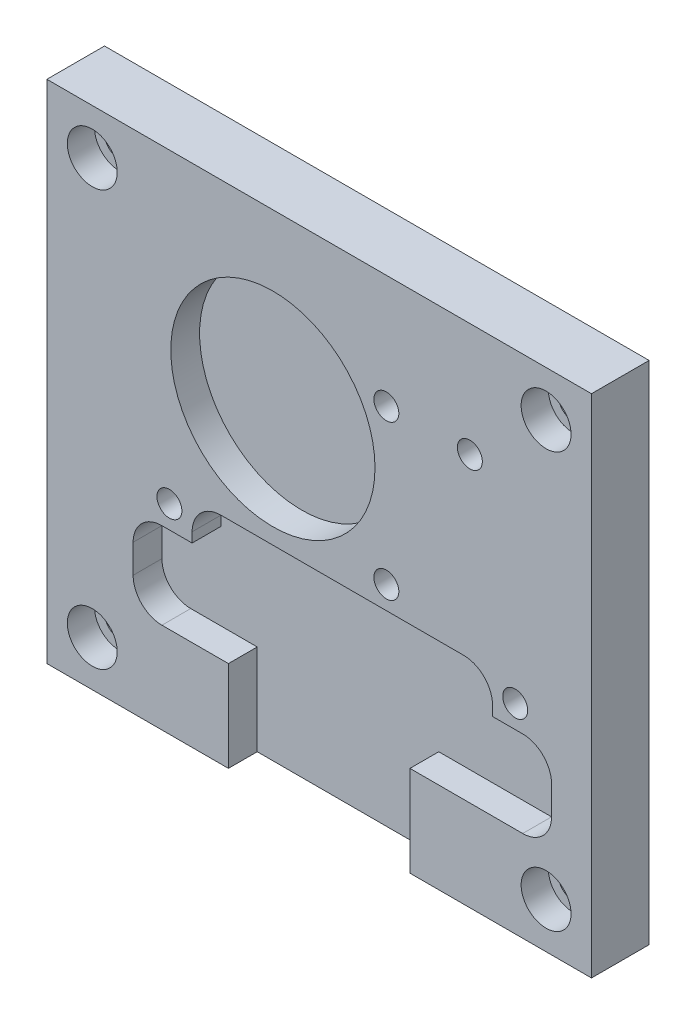
SolidWorks part; units mm, degrees
ref_plane "Front Plane" through (0, 0, 0) normal (0, 0, 1) x (1, 0, 0)
ref_plane "Top Plane" through (0, 0, 0) normal (0, 1, 0) x (1, 0, 0)
ref_plane "Right Plane" through (0, 0, 0) normal (1, 0, 0) x (0, 0, -1)
sketch "Sketch1" plane through (0, 0, 0) normal (0, 0, 1) x (1, 0, 0)
  line L0 (-28, -8.25) -> (-28, -35.75) construction
  line L1 (-60, -55.75) -> (60, -55.75)
  line L2 (-60, -55.75) -> (-60, 55.75)
  line L3 (-60, 55.75) -> (60, 55.75)
  line L4 (60, -55.75) -> (60, 55.75)
  line L5 (-60, -55.75) -> (60, 55.75) construction
  line L6 (-60, 55.75) -> (60, -55.75) construction
  line L7 (-28, -8.25) -> (38.2, -8.25) construction
  line L8 (38.2, -8.25) -> (38.2, -35.75) construction
  line L9 (-38, 55.75) -> (-38, -55.75) construction
  line L10 (48.2, 55.75) -> (48.2, -55.75) construction
  line L11 (-38, 35.75) -> (48.2, 35.75) construction
  line L12 (-28, -35.75) -> (-20, -35.75) construction
  line L13 (-20, -35.75) -> (-20, -55.75) construction
  line L14 (20, -35.75) -> (20, -55.75) construction
  line L15 (20, -35.75) -> (38.2, -35.75) construction
  line L16 (-20, -35.75) -> (20, -35.75) construction
  circle A0 centre (-50, 45.75) radius 10 construction
  circle A1 centre (-50, -45.75) radius 10 construction
  circle A2 centre (50, -45.75) radius 10 construction
  circle A3 centre (50, 45.75) radius 10 construction
  circle A4 centre (43.2, -11.75) radius 2.5 construction
  circle A5 centre (33.2, 30.75) radius 2.5 construction
  circle A6 centre (14.8, 30.75) radius 2.5 construction
  circle A7 centre (14.8, -3.25) radius 2.5 construction
  circle A8 centre (-33, -11.75) radius 2.5 construction
  circle A9 centre (-10.2, 17.75) radius 22.5 construction
  point P0 (0, 0)
  point P40 (0, -35.75)
  point P41 (0, 0)
  dimension "D2" = 20
  dimension "D3" = 5
  dimension "D4" = 45
  dimension "D1" = 100
  dimension "D5" = 10
  dimension "D6" = 18.4
  dimension "D7" = 25
  dimension "D8" = 34
  dimension "D9" = 47.8
  dimension "D10" = 8.5
  dimension "D11" = 13
  dimension "D12" = 14.8
  dimension "D13" = 5
  dimension "D14" = 5
  dimension "D15" = 5
  dimension "D16" = 5
  dimension "D17" = 5
  dimension "D18" = 18
  dimension "D19" = 27.5
  dimension "D20" = 40
extrude "Boss-Extrude1" add sketch "Sketch1" along normal blind 12.7
sketch "Sketch2" plane through (0, 0, 12.7) normal (0, 0, 1) x (1, 0, 0)
  line L0 (38.2, -8.25) -> (38.2, -35.75) construction
  line L1 (20, -35.75) -> (38.2, -35.75) construction
  line L2 (20, -35.75) -> (20, -55.75) construction
  line L3 (-28, -35.75) -> (-20, -35.75) construction
  line L4 (-20, -35.75) -> (-20, -55.75) construction
  line L5 (-28, -8.25) -> (38.2, -8.25) construction
  line L6 (-28, -8.25) -> (-28, -35.75) construction
  line L7 (38.2, -8.25) -> (38.2, -16.75)
  line L8 (20, -35.75) -> (38.2, -35.75)
  line L9 (20, -35.75) -> (20, -55.75)
  line L10 (-28, -35.75) -> (-20, -35.75)
  line L11 (-20, -35.75) -> (-20, -55.75)
  line L12 (-28, -8.25) -> (38.2, -8.25)
  line L13 (-28, -8.25) -> (-28, -16.75)
  line L14 (-20, -55.75) -> (20, -55.75)
  line L15 (-28, -35.75) -> (-41, -35.75)
  line L16 (-41, -35.75) -> (-41, -16.75)
  line L17 (-41, -16.75) -> (-28, -16.75)
  line L18 (38.2, -35.75) -> (51.2, -35.75)
  line L19 (51.2, -35.75) -> (51.2, -16.75)
  line L20 (51.2, -16.75) -> (38.2, -16.75)
  line L21 (-38, 55.75) -> (-38, -55.75) construction
  circle A0 centre (-10.2, 17.75) radius 22.5 construction
  circle A1 centre (-10.2, 17.75) radius 22.5
  circle A2 centre (-33, -11.75) radius 5 construction
  dimension "D1" = 3
extrude "Cut-Extrude1" cut sketch "Sketch2" against normal blind 6.35
fillet "Fillet1" radius 6.35 6 edges at (38.2, -8.25, 9.525) (51.2, -16.75, 9.525) (51.2, -35.75, 9.525) (-41, -35.75, 9.525) (-41, -16.75, 9.525) (-28, -8.25, 9.525)
hole_wizard "CBORE for M5 SHCS1" positions "Sketch3" profile "Sketch4" counterbore size "M5" standard "ANSI Metric" end condition through all
sketch "Sketch3" plane through (0, 0, 0) normal (0, 0, -1) x (-1, 0, 0)
  point P0 (-33.2, 30.75)
  point P3 (-14.8, 30.75)
  point P6 (-14.8, -3.25)
  point P9 (-43.2, -11.75)
  point P12 (33, -11.75)
sketch "Sketch4" plane through (33.2, 30.75, 0) normal (1, 0, 0) x (0, 1, 0)
  line L0 (0, 0) -> (0, 12.7)
  line L1 (0, 12.7) -> (2.75, 12.7)
  line L3 (2.75, 12.7) -> (2.75, 5)
  line L4 (2.75, 5) -> (5, 5)
  line L5 (5, 5) -> (5, 0)
  line L7 (5, 0) -> (0, 0)
  line L11 (0, -6.35) -> (0, 107.95) construction
  dimension "Thru Hole Dia." = 5.5
  dimension "Thru Hole Depth" = 12.7
  dimension "C'Bore Dia." = 10
  dimension "C'Bore Depth" = 5
hole_wizard "CBORE for M6 SHCS1" positions "Sketch5" profile "Sketch6" counterbore size "M6" standard "ANSI Metric" end condition through all
sketch "Sketch5" plane through (0, 0, 12.7) normal (0, 0, 1) x (1, 0, 0)
  point P0 (-50, 45.75)
  point P3 (50, 45.75)
  point P6 (50, -45.75)
  point P9 (-50, -45.75)
sketch "Sketch6" plane through (-50, 45.75, 12.7) normal (1, 0, 0) x (0, -1, 0)
  line L0 (0, 0) -> (0, 12.7)
  line L1 (0, 12.7) -> (3.3, 12.7)
  line L3 (3.3, 12.7) -> (3.3, 6)
  line L4 (3.3, 6) -> (5.5, 6)
  line L5 (5.5, 6) -> (5.5, 0)
  line L7 (5.5, 0) -> (0, 0)
  line L11 (0, -6.35) -> (0, 107.95) construction
  dimension "Thru Hole Dia." = 6.6
  dimension "Thru Hole Depth" = 12.7
  dimension "C'Bore Dia." = 11
  dimension "C'Bore Depth" = 6
